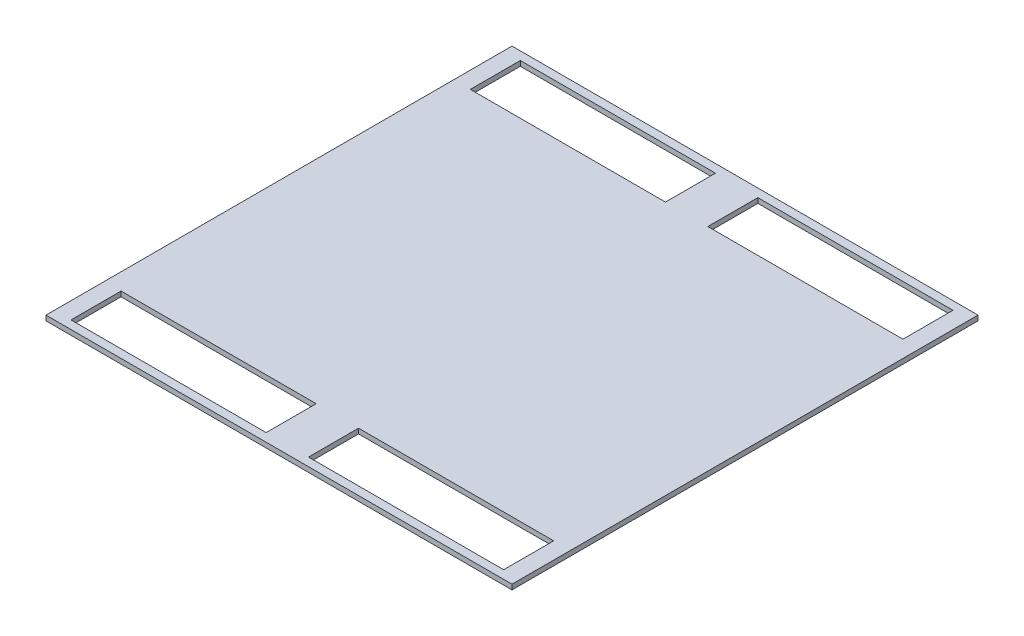
SolidWorks part; units mm, degrees
material "ENPH 253 Hardboard"
ref_plane "Front Plane" through (0, 0, 0) normal (0, 0, 1) x (1, 0, 0)
ref_plane "Top Plane" through (0, 0, 0) normal (0, 1, 0) x (1, 0, 0)
ref_plane "Right Plane" through (0, 0, 0) normal (1, 0, 0) x (0, 0, -1)
sketch "Sketch1" plane through (0, 0, 0) normal (0, 1, 0) x (1, 0, 0)
  line L0 (0, -139.7) -> (0, 139.7) construction
  line L1 (-139.7, 139.7) -> (139.7, 139.7)
  line L2 (-139.7, 139.7) -> (-139.7, -139.7)
  line L3 (-139.7, -139.7) -> (139.7, -139.7)
  line L4 (139.7, 139.7) -> (139.7, -139.7)
  line L5 (-139.7, 139.7) -> (139.7, -139.7) construction
  line L6 (-139.7, -139.7) -> (139.7, 139.7) construction
  line L7 (-129.7, 134.7) -> (-12.7, 134.7)
  line L8 (-129.7, 134.7) -> (-129.7, 104.7)
  line L9 (-129.7, 104.7) -> (-12.7, 104.7)
  line L10 (-12.7, 134.7) -> (-12.7, 104.7)
  line L12 (-139.7, 0) -> (139.7, 0) construction
  line L14 (129.7, 104.7) -> (12.7, 104.7)
  line L15 (12.7, 134.7) -> (12.7, 104.7)
  line L16 (129.7, 134.7) -> (12.7, 134.7)
  line L17 (129.7, 134.7) -> (129.7, 104.7)
  line L18 (129.7, -134.7) -> (129.7, -104.7)
  line L19 (129.7, -134.7) -> (12.7, -134.7)
  line L20 (12.7, -134.7) -> (12.7, -104.7)
  line L21 (129.7, -104.7) -> (12.7, -104.7)
  line L22 (-129.7, -104.7) -> (-12.7, -104.7)
  line L23 (-12.7, -134.7) -> (-12.7, -104.7)
  line L24 (-129.7, -134.7) -> (-12.7, -134.7)
  line L25 (-129.7, -134.7) -> (-129.7, -104.7)
  point P0 (0, 0)
  dimension "D1" = 279.4
  dimension "D2" = 279.4
  dimension "D3" = 5
  dimension "D4" = 30
  dimension "D5" = 117
  dimension "D6" = 10
extrude "Boss-Extrude1" add sketch "Sketch1" along normal blind 3
